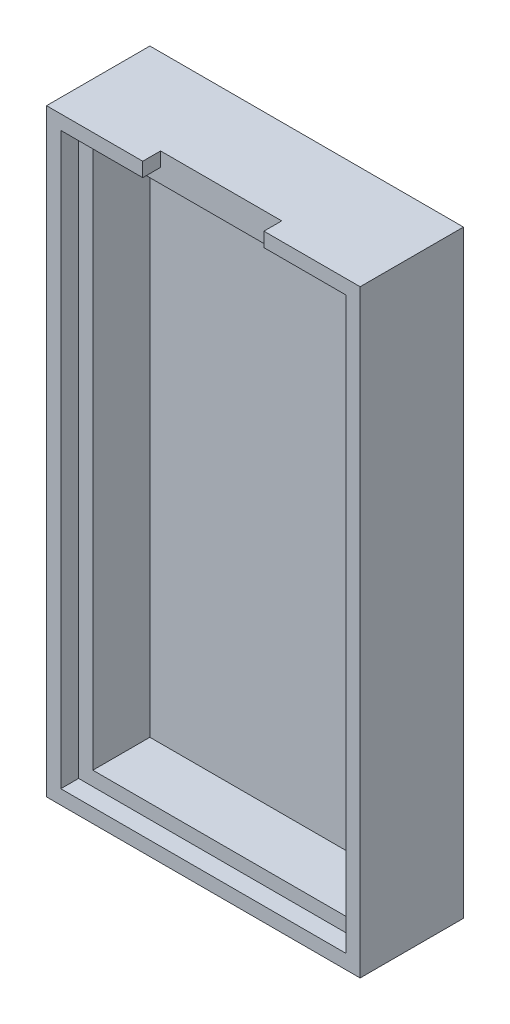
SolidWorks part; units mm, degrees
ref_plane "Front Plane" through (0, 0, 0) normal (0, 0, 1) x (1, 0, 0)
ref_plane "Top Plane" through (0, 0, 0) normal (0, 1, 0) x (1, 0, 0)
ref_plane "Right Plane" through (0, 0, 0) normal (1, 0, 0) x (0, 0, -1)
sketch "Sketch1" plane through (0, 0, 0) normal (0, 0, 1) x (1, 0, 0)
  line L1 (-13.97, 26.67) -> (13.97, 26.67)
  line L2 (-13.97, 26.67) -> (-13.97, -26.67)
  line L3 (-13.97, -26.67) -> (13.97, -26.67)
  line L4 (13.97, 26.67) -> (13.97, -26.67)
  point P4 (0, 26.67)
  point P6 (-13.97, 0)
  dimension "D1" = 53.34
  dimension "D2" = 27.94
extrude "Boss-Extrude1" add sketch "Sketch1" along normal mid plane 9.2075
shell "Shell1" thickness 2.54
sketch "Sketch2" plane through (0, 26.67, 0) normal (0, 1, 0) x (1, 0, 0)
  line L0 (13.97, -4.6037) -> (-13.97, -4.6037) construction
  line L1 (-5.3975, -4.6037) -> (5.3975, -4.6037)
  line L2 (-5.3975, -4.6037) -> (-5.3975, -3.0162)
  line L3 (-5.3975, -3.0162) -> (5.3975, -3.0162)
  line L4 (5.3975, -4.6037) -> (5.3975, -3.0162)
  point P6 (0, -3.0162)
  dimension "D1" = 10.795
  dimension "D2" = 1.5875
extrude "Cut-Extrude1" cut sketch "Sketch2" against normal up to surface (2.54 mm away) up to face at (0, 24.13, 1.27)
sketch "Sketch3" plane through (0, 0, 4.6037) normal (0, 0, 1) x (1, 0, 0)
  line L17 (12.7, -25.4) -> (12.7, 25.4)
  line L18 (-12.7, -25.4) -> (12.7, -25.4)
  line L19 (-12.7, 25.4) -> (-12.7, -25.4)
  line L20 (12.7, 25.4) -> (-12.7, 25.4)
  line L21 (12.7, -25.4) -> (12.7, 25.4)
  line L22 (-12.7, -25.4) -> (12.7, -25.4)
  line L23 (-12.7, 25.4) -> (-12.7, -25.4)
  line L24 (12.7, 25.4) -> (-12.7, 25.4)
  dimension "D1" = 1.27
extrude "Cut-Extrude2" cut sketch "Sketch3" against normal up to surface (1.5875 mm away) up to face at (0, 25.4, 3.0162)
